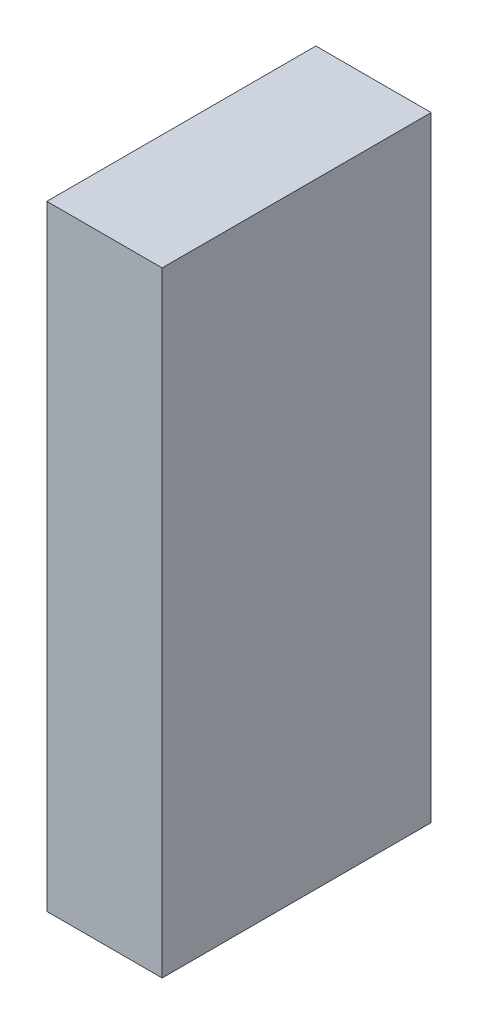
SolidWorks part; units mm, degrees
ref_plane "Front Plane" through (0, 0, 0) normal (0, 0, 1) x (1, 0, 0)
ref_plane "Top Plane" through (0, 0, 0) normal (0, 1, 0) x (1, 0, 0)
ref_plane "Right Plane" through (0, 0, 0) normal (1, 0, 0) x (0, 0, -1)
sketch "Sketch1" plane through (0, 0, 0) normal (0, 1, 0) x (1, 0, 0)
  line L1 (0, 0) -> (38.1, 0)
  line L2 (0, 0) -> (0, 88.9)
  line L3 (0, 88.9) -> (38.1, 88.9)
  line L4 (38.1, 0) -> (38.1, 88.9)
  dimension "D1" = 88.9
  dimension "D2" = 38.1
extrude "Boss-Extrude1" add sketch "Sketch1" along normal blind 203.2
